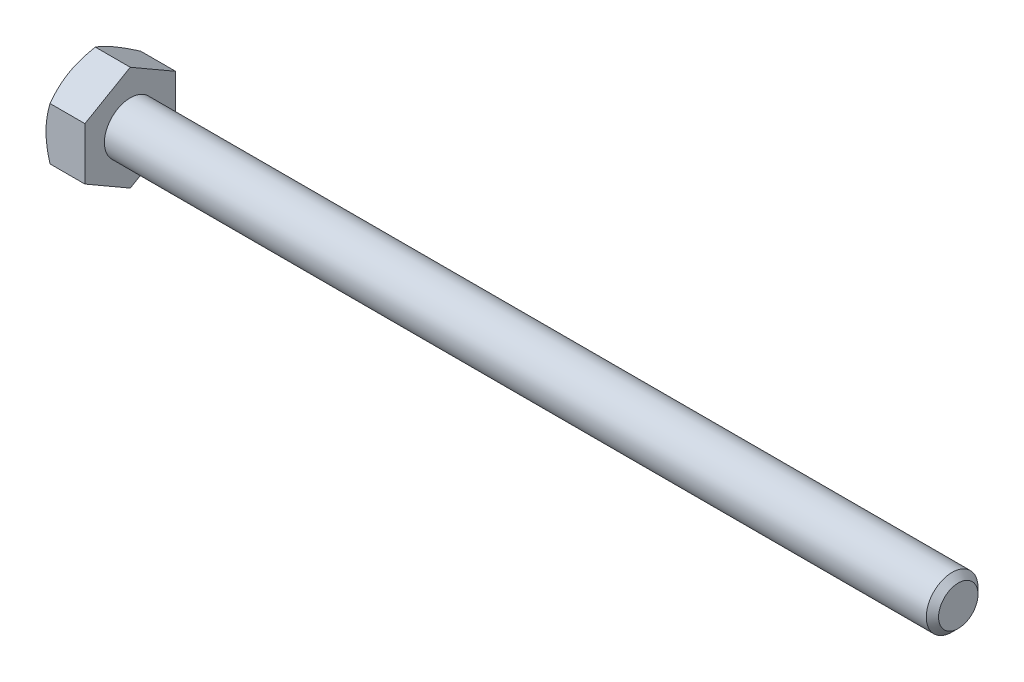
SolidWorks part; units mm, degrees
ref_plane "Plane1" through (0, 0, 0) normal (0, 0, 1) x (1, 0, 0)
ref_plane "Plane2" through (0, 0, 0) normal (0, 1, 0) x (1, 0, 0)
ref_plane "Plane3" through (0, 0, 0) normal (1, 0, 0) x (0, 0, -1)
sketch "Sketch1" plane through (0, 0, 0) normal (1, 0, 0) x (0, 0, -1)
  line L0 (5.5626, 3.2116) -> (5.5626, -3.2116)
  line L1 (-5.5626, 3.2116) -> (-5.5626, -3.2116)
  line L2 (5.5626, -3.2116) -> (0, -6.4231)
  line L3 (0, -6.4231) -> (-5.5626, -3.2116)
  line L4 (5.5626, 3.2116) -> (0, 6.4231)
  line L5 (0, 6.4231) -> (-5.5626, 3.2116)
  dimension "Width_flats" = 11.1252
  dimension "D2" = 120
  dimension "D3" = 5.5626
  dimension "D4" = 5.5626
  dimension "D5" = 5.5626
extrude "BaseHead" add sketch "Sketch1" along normal blind 4.7752
sketch "BodySke" plane through (0, 0, 0) normal (0, 0, 1) x (1, 0, 0)
  line L0 (0, 3.2116) -> (0, -3.2116) construction
  line L1 (0, 0) -> (106.3752, 0)
  line L2 (0, 0) -> (0, 3.175)
  line L3 (0, 3.175) -> (105.6195, 3.175)
  line L4 (106.3752, 0) -> (106.3752, 2.4193)
  line L5 (4.7752, 6.4231) -> (4.7752, 3.2116) construction
  line L6 (106.3752, 2.4193) -> (105.6195, 3.175)
  line L7 (0, 0) -> (96.52, 0) construction
  line L8 (106.3752, -2.4193) -> (105.6195, -3.175) construction
  line L9 (0, -3.175) -> (105.6195, -3.175) construction
  line L10 (6.0452, 15.24) -> (6.0452, -2.54) construction
  line L11 (87.3252, 15.24) -> (87.3252, -2.54) construction
  line L12 (4.7752, 3.2116) -> (4.7752, -3.2116) construction
  dimension "Length" = 101.6
  dimension "Body_ch_ang" = 45
  dimension "Diameter" = 6.35
  dimension "Minor_dia" = 4.8387
  dimension "Advance" = 1.27
  dimension "Thread_nom" = 19.05
revolve "BaseBody" add sketch "BodySke" angle 360 about L7
cosmetic thread "ThreadCosmetic" [suppressed] parameters "Thread_length"=19.05, "Thread_minor"=4.8387
sketch "Sketch3" plane through (0, 0, 0) normal (0, 0, 1) x (1, 0, 0)
  line L0 (0, 5.5626) -> (4.163, 12.7731)
  line L1 (0, 6.4231) -> (0, 3.2116) construction
  line L2 (4.163, 12.7731) -> (4.163, 19.1231)
  line L3 (4.163, 19.1231) -> (-12.7, 19.1231)
  line L4 (-12.7, 19.1231) -> (-12.7, 5.5626)
  line L5 (-12.7, 5.5626) -> (0, 5.5626)
  line L6 (0, 0) -> (99.06, 0) construction
  line L7 (4.7752, 6.4231) -> (0, 6.4231) construction
  dimension "D1" = 5.5626
  dimension "D2" = 6.35
  dimension "D3" = 12.7
  dimension "D4" = 6.35
  dimension "Head_ch_ang" = 30
revolve "HeadChamfer" cut sketch "Sketch3" angle 360 about L6
fillet "HeadFillet" [suppressed] radius 0.762
sketch "ThdSchSke" plane through (0, 0, 0) normal (0, 0, 1) x (1, 0, 0)
  line L0 (87.3252, -2.4193) -> (86.7961, -3.175)
  line L1 (87.3252, -2.4193) -> (87.8543, -3.175)
  line L2 (87.8543, -3.175) -> (87.8543, -3.9687)
  line L3 (-3.175, 0) -> (5.1513, 0) construction
  line L5 (87.8543, -3.9687) -> (86.7961, -3.9687)
  line L6 (86.7961, -3.9687) -> (86.7961, -3.175)
  dimension "Thread_minor" = 4.8387
  dimension "Diameter" = 6.35
  dimension "Start" = 87.3252
  dimension "SideAngle" = 55
  dimension "VeeAngle" = 70
  dimension "Overcut" = 7.9375
revolve "ThreadSchematic" [suppressed] cut sketch "ThdSchSke" angle 360 about L3
pattern_linear "ThdSchPat" [suppressed]
equation "\"D3@Sketch1\" = \"Width_flats@Sketch1\" / 2"
equation "\"D4@Sketch1\" = \"D3@Sketch1\""
equation "\"D5@Sketch1\" = \"D4@Sketch1\""
equation "\"Thread_minor@ThreadCosmetic\" = \"Minor_dia@BodySke\""
equation "\"D1@Sketch3\" = \"Width_flats@Sketch1\" / 2"
equation "\"Thread_length@ThreadCosmetic\" = ((sgn( (\"Length@BodySke\" - \"Advance@BodySke\" ) - \"Thread_nom@BodySke\" )-1)*( (\"Length@BodySke\" - \"Advance@BodySke\" ) - \"Thread_nom@BodySke\" ))/-2+ \"Thread_nom@BodySke\""
equation "\"Thread_minor@ThdSchSke\" = \"Minor_dia@BodySke\""
equation "\"Diameter@ThdSchSke\" = \"Diameter@BodySke\""
equation "\"Overcut@ThdSchSke\" = \"Diameter@BodySke\" * 1.25"
equation "\"Start@ThdSchSke\" = \"Head_ht@BaseHead\" + \"Length@BodySke\" - \"Thread_length@ThreadCosmetic\"  '---Non-countersunk---"
equation "\"Num_threads@ThdSchPat\" = int( \"Thread_length@ThreadCosmetic\" / \"Advance@BodySke\" + 0.999 )  + 1"
equation "\"Advance@ThdSchPat\" = \"Thread_length@ThreadCosmetic\" /  (\"Num_threads@ThdSchPat\" - 1) 'relax it"
equation "\"Num_threads@ThdSchPat\" = \"Num_threads@ThdSchPat\" - sgn( \"Num_threads@ThdSchPat\" - 1) '---chamfered tips only---"
